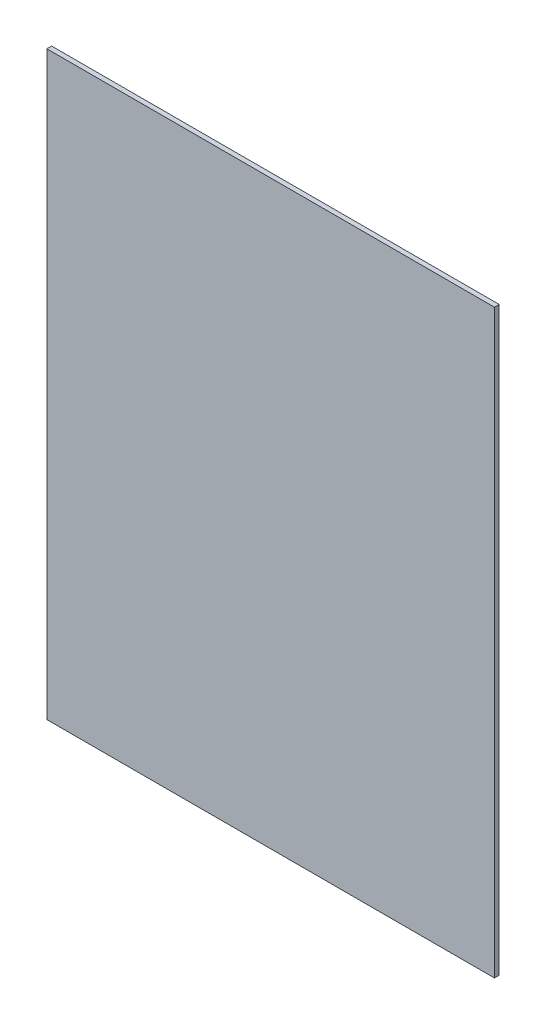
SolidWorks part; units mm, degrees
material "PC High Viscosity"
ref_plane "Front Plane" through (0, 0, 0) normal (0, 0, 1) x (1, 0, 0)
ref_plane "Top Plane" through (0, 0, 0) normal (0, 1, 0) x (1, 0, 0)
ref_plane "Right Plane" through (0, 0, 0) normal (1, 0, 0) x (0, 0, -1)
sketch "Sketch1" plane through (0, 0, 0) normal (0, 0, 1) x (1, 0, 0)
  line L1 (-298.45, 0) -> (298.45, 0)
  line L2 (-298.45, 0) -> (-298.45, 774.7)
  line L3 (-298.45, 774.7) -> (298.45, 774.7)
  line L4 (298.45, 0) -> (298.45, 774.7)
  dimension "D1" = 596.9
  dimension "D2" = 774.7
extrude "Boss-Extrude1" add sketch "Sketch1" along normal blind 6.35
